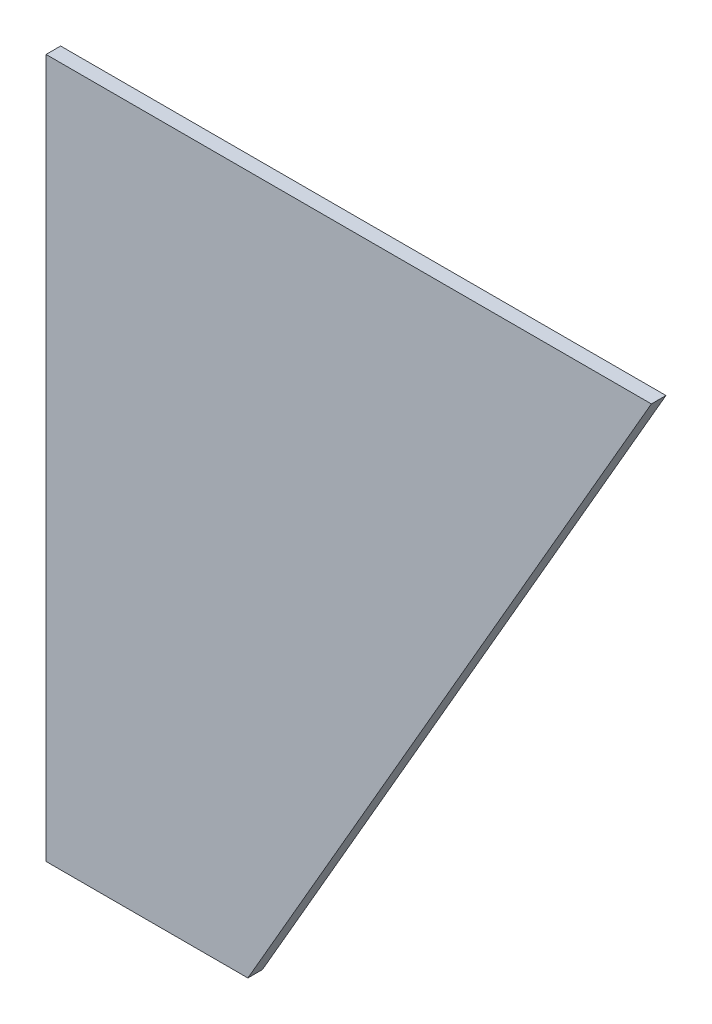
SolidWorks part; units mm, degrees
ref_plane "Front Plane" through (0, 0, 0) normal (0, 0, 1) x (1, 0, 0)
ref_plane "Top Plane" through (0, 0, 0) normal (0, 1, 0) x (1, 0, 0)
ref_plane "Right Plane" through (0, 0, 0) normal (1, 0, 0) x (0, 0, -1)
sketch "Sketch1" plane through (0, 0, 0) normal (0, 0, 1) x (1, 0, 0)
  line L1 (8.2388, 74.0349) -> (-63.1812, -49.6751)
  line L2 (-63.1812, -49.6751) -> (-104.6812, -49.6751)
  line L3 (-104.6812, -49.6751) -> (-104.6812, 74.0349)
  line L4 (-104.6812, 74.0349) -> (-104.6812, 94.0349)
  line L5 (-104.6812, 94.0349) -> (19.7852, 94.0349)
  line L6 (8.2388, 74.0349) -> (19.7852, 94.0349)
  dimension "D1" = 112.92
  dimension "D2" = 123.71
  dimension "D3" = 41.5
  dimension "D4" = 20
extrude "Boss-Extrude1" add sketch "Sketch1" along normal blind 3
